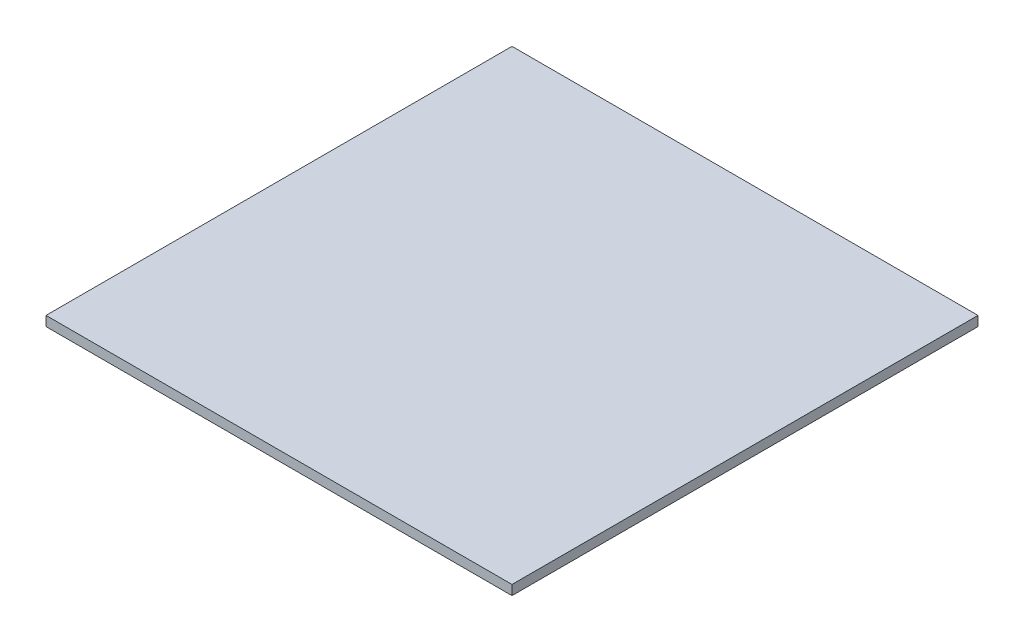
SolidWorks part; units mm, degrees
ref_plane "Front Plane" through (0, 0, 0) normal (0, 0, 1) x (1, 0, 0)
ref_plane "Top Plane" through (0, 0, 0) normal (0, 1, 0) x (1, 0, 0)
ref_plane "Right Plane" through (0, 0, 0) normal (1, 0, 0) x (0, 0, -1)
sketch "Sketch1" plane through (0, 0, 0) normal (0, 0, 1) x (1, 0, 0)
  line L0 (0, 3.175) -> (0, -3.175)
  line L1 (-152.4, 0) -> (152.4, 0) construction
  point P6 (0, 0)
  dimension "Width" = 304.8
  dimension "Thk" = 6.35
sketch "Sketch2" plane through (0, 0, 0) normal (1, 0, 0) x (0, 0, -1)
  line L0 (152.4, 0) -> (-152.4, 0)
  point P4 (0, 0)
  dimension "Length" = 304.8
sketch "Sketch3" plane through (0, 0, 0) normal (0, 0, 1) x (1, 0, 0)
  line L1 (152.4, 3.175) -> (-152.4, 3.175)
  line L2 (152.4, 3.175) -> (152.4, -3.175)
  line L3 (152.4, -3.175) -> (-152.4, -3.175)
  line L4 (-152.4, 3.175) -> (-152.4, -3.175)
  line L5 (152.4, 3.175) -> (-152.4, -3.175) construction
  line L6 (152.4, -3.175) -> (-152.4, 3.175) construction
  point P0 (0, 0)
extrude "Boss-Extrude1" add sketch "Sketch3" along normal up to vertex (152.4 mm away) and the other way up to vertex (152.4 mm away) up to point (0, 0, 152.4) other way up to point (0, 0, -152.4)
